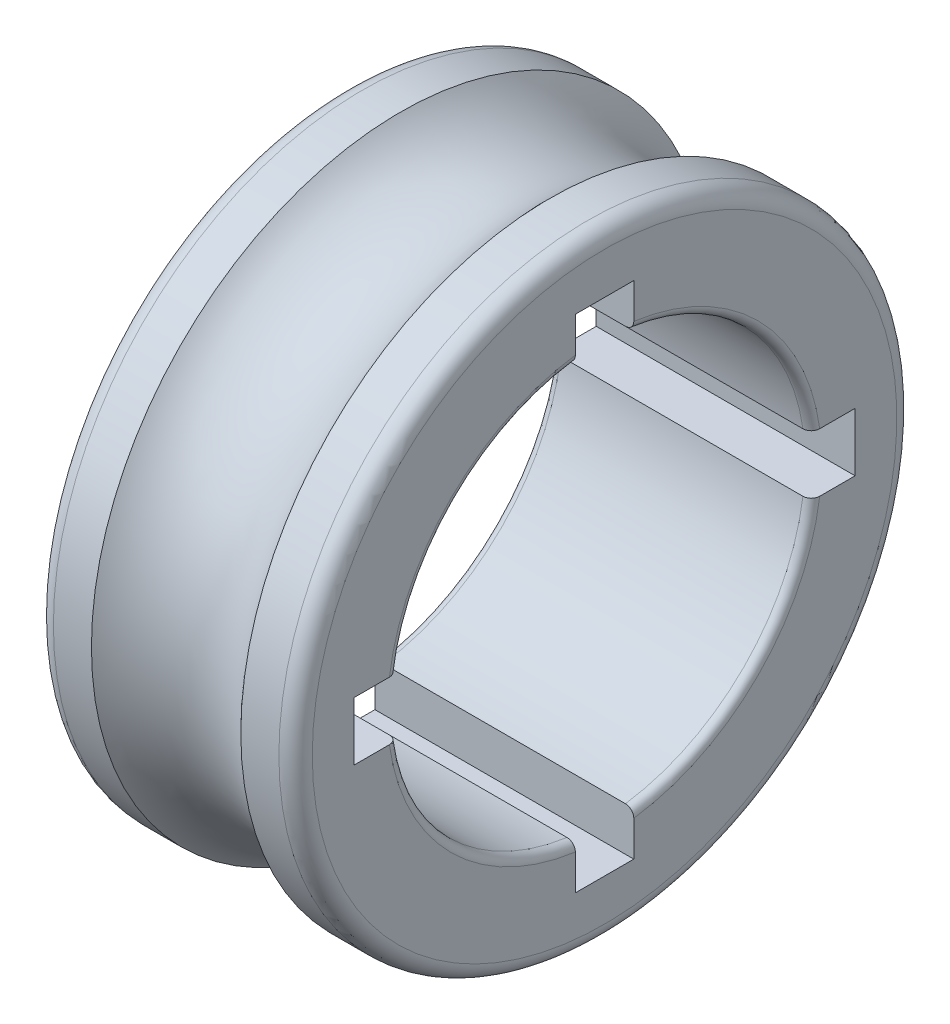
SolidWorks part; units mm, degrees
ref_plane "Front Plane" through (0, 0, 0) normal (0, 0, 1) x (1, 0, 0)
ref_plane "Top Plane" through (0, 0, 0) normal (0, 1, 0) x (1, 0, 0)
ref_plane "Right Plane" through (0, 0, 0) normal (1, 0, 0) x (0, 0, -1)
sketch "Sketch1" plane through (0, 0, 0) normal (0, 0, 1) x (1, 0, 0)
  line L0 (0, 0) -> (0, 34452.5024) construction
  line L1 (0, 0) -> (34452.5024, 0) construction
  line L2 (-13.5, 37) -> (-8.9443, 37)
  line L3 (-14.5, 25) -> (14.5, 25)
  line L4 (-15.5, 35) -> (-15.5, 26)
  line L5 (15.5, 35) -> (15.5, 26)
  line L6 (8.9443, 37) -> (13.5, 37)
  arc A0 (-8.9443, 37) -> (8.9443, 37) centre (0, 45) ccw
  arc A1 (13.5, 37) -> (15.5, 35) centre (13.5, 35) cw
  arc A2 (-13.5, 37) -> (-15.5, 35) centre (-13.5, 35) ccw
  arc A3 (14.5, 25) -> (15.5, 26) centre (14.5, 26) ccw
  arc A4 (-14.5, 25) -> (-15.5, 26) centre (-14.5, 26) cw
  point P14 (15.5, 37)
  point P17 (-15.5, 37)
  dimension "D5" = 12
  dimension "D6" = 2
  dimension "D7" = 1
  dimension "D1" = 31
  dimension "D2" = 50
  dimension "D3" = 74
  dimension "D4" = 8
revolve "Revolve1" add sketch "Sketch1" angle 360 about L1
sketch "Sketch2" plane through (0, 0, 0) normal (1, 0, 0) x (0, 0, -1)
  line L1 (3.5, -30) -> (-3.5, -30)
  line L2 (3.5, -30) -> (3.5, 30)
  line L3 (3.5, 30) -> (-3.5, 30)
  line L4 (-3.5, -30) -> (-3.5, 30)
  line L5 (3.5, -30) -> (-3.5, 30) construction
  line L6 (3.5, 30) -> (-3.5, -30) construction
  point P0 (0, 0)
  dimension "D1" = 7
  dimension "D2" = 30
extrude "Cut-Extrude1" cut sketch "Sketch2" against normal through all both and the other way through all
pattern_circular "CirPattern1" count 4 over 360 about axis through (0, 0, 0) along (1, 0, 0) of "Cut-Extrude1"
